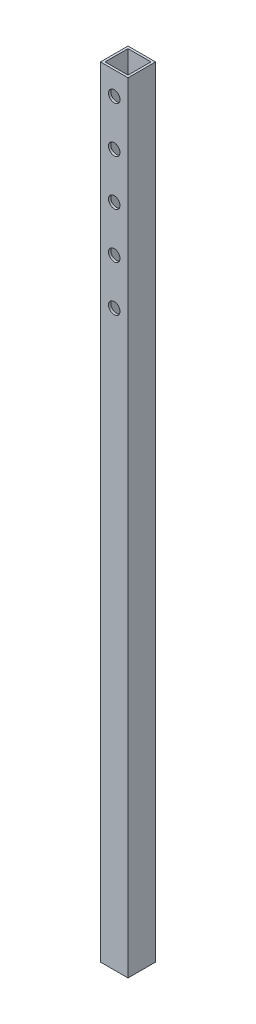
SolidWorks part; units mm, degrees
material "1060 Alloy"
ref_plane "Front" through (0, 0, 0) normal (0, 0, 1) x (1, 0, 0)
ref_plane "Top" through (0, 0, 0) normal (0, 1, 0) x (1, 0, 0)
ref_plane "Right" through (0, 0, 0) normal (1, 0, 0) x (0, 0, -1)
sketch "Sketch1" plane through (0, 0, 0) normal (0, 1, 0) x (1, 0, 0)
  line L1 (-12.7, 12.7) -> (12.7, 12.7)
  line L2 (-12.7, 12.7) -> (-12.7, -12.7)
  line L3 (-12.7, -12.7) -> (12.7, -12.7)
  line L4 (12.7, 12.7) -> (12.7, -12.7)
  point P4 (0, 12.7)
  point P6 (-12.7, 0)
  dimension "D1" = 25.4
  dimension "D2" = 25.4
extrude "Extrude-Thin1" add sketch "Sketch1" along normal blind 863.6 thin thin type one direction wall 2.54
sketch "Sketch2" plane through (0, 0, 15.24) normal (0, 0, 1) x (1, 0, 0)
  line L0 (-15.24, 863.6) -> (15.24, 863.6) construction
  circle A0 centre (0, 838.2) radius 6.35
  point P4 (0, 863.6)
  dimension "D1" = 12.7
  dimension "D2" = 25.4
extrude "Cut-Extrude1" cut sketch "Sketch2" against normal through all
pattern_linear "LPattern1" count 5 spacing 50.8 along (0, -1, 0) of "Cut-Extrude1"
